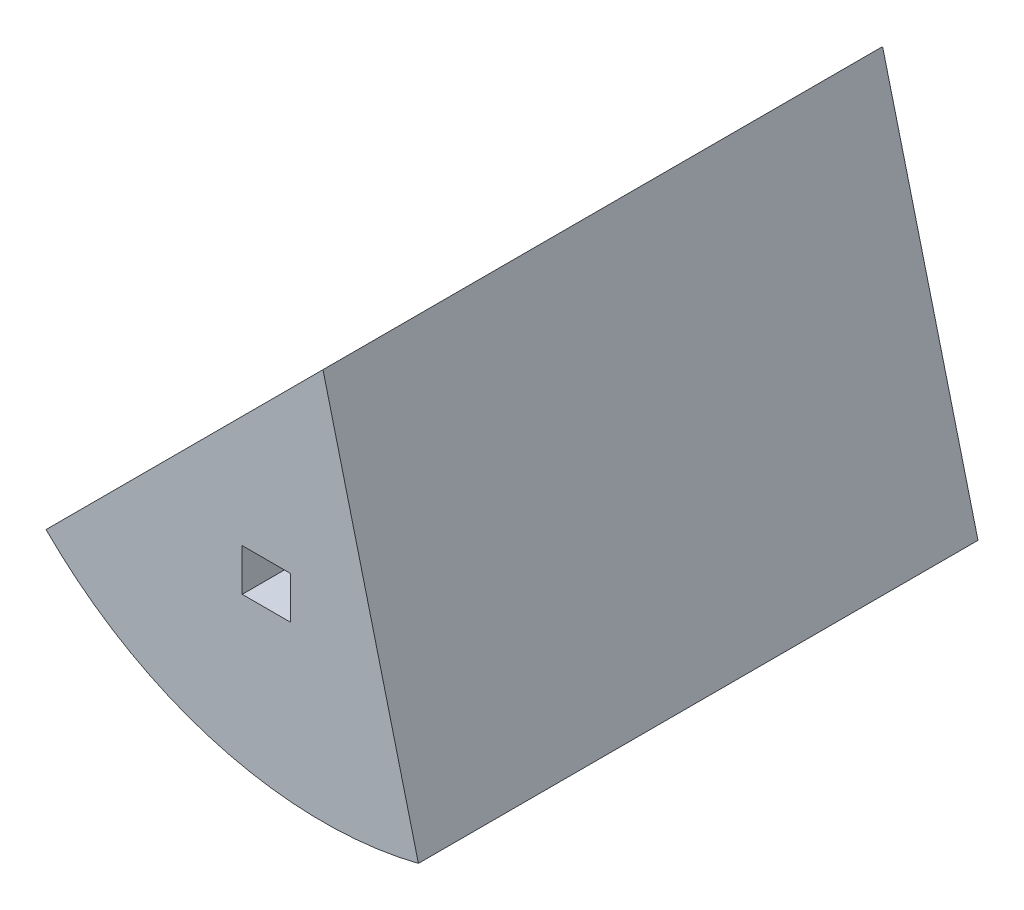
SolidWorks part; units mm, degrees
ref_plane "Ön Düzlem" through (0, 0, 0) normal (0, 0, 1) x (1, 0, 0)
ref_plane "Üst Düzlem" through (0, 0, 0) normal (0, 1, 0) x (1, 0, 0)
ref_plane "Sağ Düzlem" through (0, 0, 0) normal (1, 0, 0) x (0, 0, -1)
sketch "Çizim1" plane through (0, 0, 0) normal (0, 0, 1) x (1, 0, 0)
  line L0 (0, 0) -> (-24.7487, -24.7487)
  line L1 (0, 0) -> (8.5246, -33.946)
  arc A0 (-24.7487, -24.7487) -> (8.5246, -33.946) centre (0, 0) ccw
  circle A1 centre (-5.0543, -19.1086) radius 1.5
  dimension "D2" = 3
  dimension "D1" = 35
  dimension "D3" = 33.946
  dimension "D4" = 24.7487
extrude "Yükseklik-Ekstrüzyon1" add sketch "Çizim1" along normal blind 50
sketch "Çizim2" plane through (0, 0, 50) normal (0, 0, 1) x (1, 0, 0)
  line L1 (-7.2165, -20.9937) -> (-2.8921, -20.9937)
  line L2 (-7.2165, -20.9937) -> (-7.2165, -17.2235)
  line L3 (-7.2165, -17.2235) -> (-2.8921, -17.2235)
  line L4 (-2.8921, -20.9937) -> (-2.8921, -17.2235)
  line L5 (-7.2165, -20.9937) -> (-2.8921, -17.2235) construction
  line L6 (-7.2165, -17.2235) -> (-2.8921, -20.9937) construction
  point P0 (-5.0543, -19.1086)
extrude "Kes-Ekstrüzyon1" cut sketch "Çizim2" against normal blind 50
